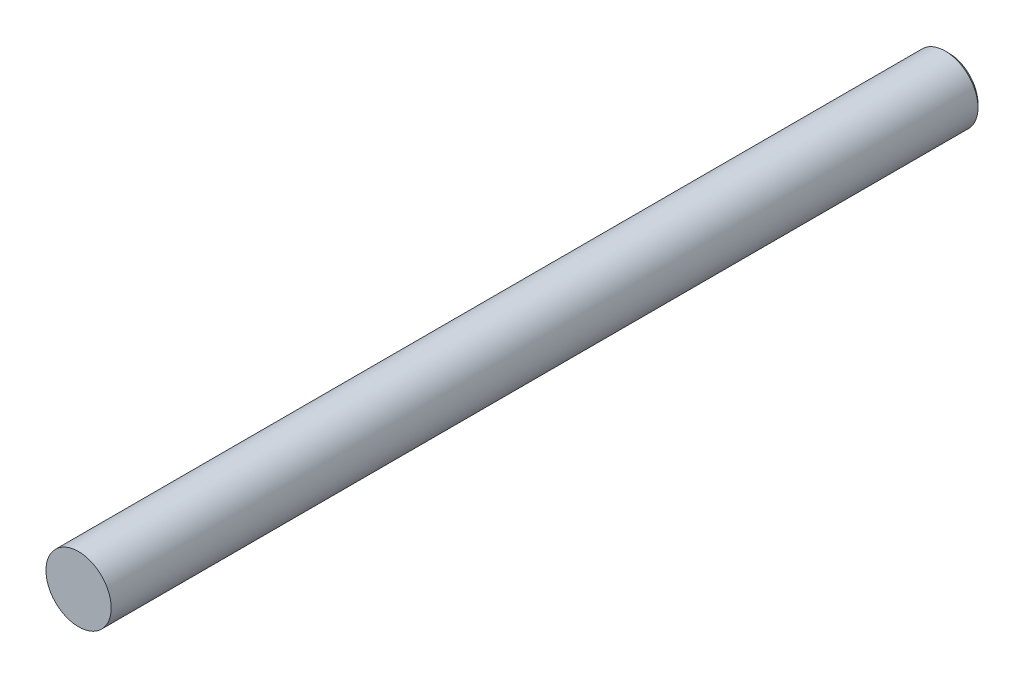
SolidWorks part; units mm, degrees
material "AISI 304"
ref_plane "Front Plane" through (0, 0, 0) normal (0, 0, 1) x (1, 0, 0)
ref_plane "Top Plane" through (0, 0, 0) normal (0, 1, 0) x (1, 0, 0)
ref_plane "Right Plane" through (0, 0, 0) normal (1, 0, 0) x (0, 0, -1)
sketch "Sketch1" plane through (0, 0, 0) normal (0, 0, 1) x (1, 0, 0)
  circle A0 centre (0, 0) radius 3
  dimension "D1" = 6
extrude "Boss-Extrude1" add sketch "Sketch1" along normal mid plane 80 contours A0
cosmetic thread "Cosmetic Thread4" parameters "D1"=5, "D2"=4.891
chamfer "Chamfer1" distance 0.3 angle 45 1 edges at (3, 0, -40)
